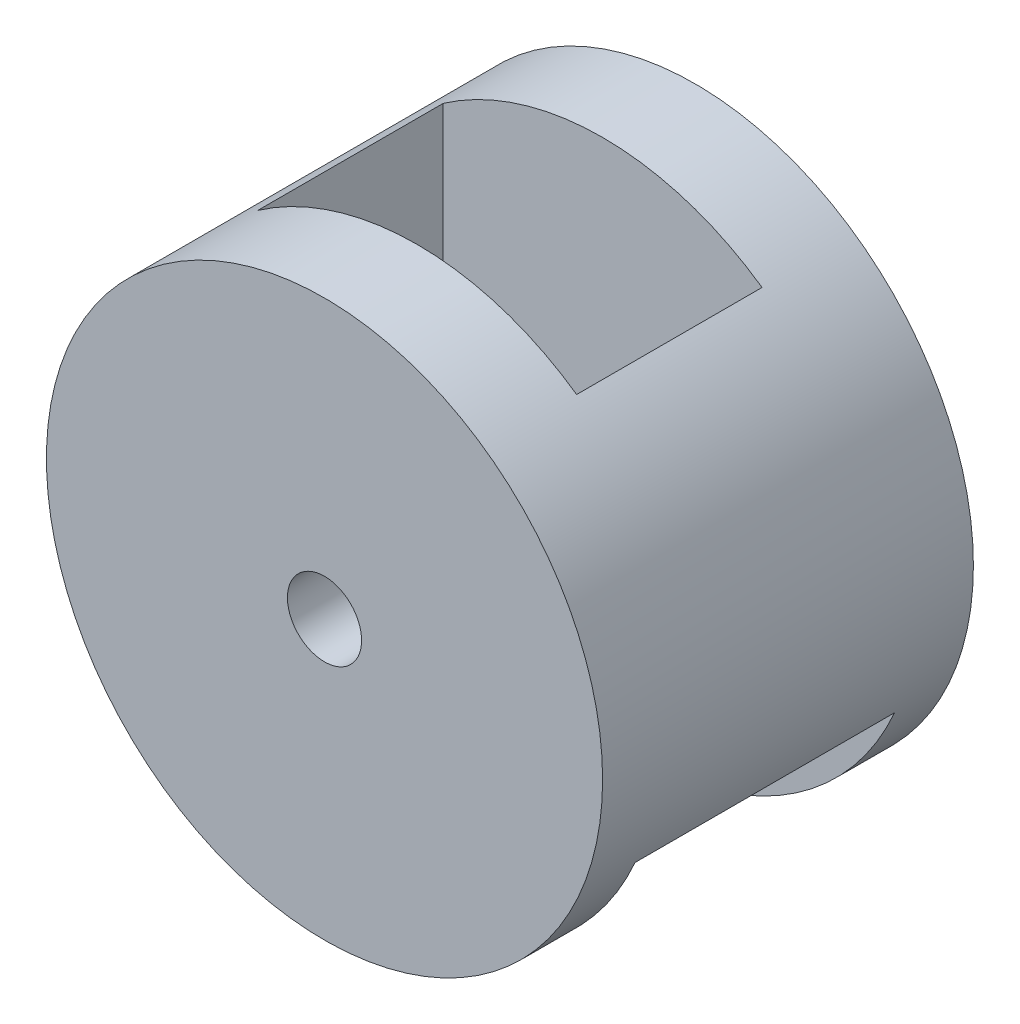
SolidWorks part; units mm, degrees
ref_plane "前视基准面" through (0, 0, 0) normal (0, 0, 1) x (1, 0, 0)
ref_plane "上视基准面" through (0, 0, 0) normal (0, 1, 0) x (1, 0, 0)
ref_plane "右视基准面" through (0, 0, 0) normal (1, 0, 0) x (0, 0, -1)
sketch "草图1" plane through (0, 0, 0) normal (0, 0, 1) x (1, 0, 0)
  circle A0 centre (0, 0) radius 7.5
  dimension "D1" = 15
extrude "凸台-拉伸1" add sketch "草图1" along normal blind 10
ref_plane "基准面4" through (0, 0, 2.5) normal (0, 0, -1) x (-1, 0, 0)
sketch "草图2" plane through (0, 0, 2.5) normal (0, 0, -1) x (-1, 0, 0)
  line L0 (-4.3, 0) -> (-4.3, 6.1449)
  line L1 (4.3, 0) -> (4.3, 6.1449)
  arc A0 (-4.3, 0) -> (4.3, 0) centre (0, 0) ccw
  circle A1 centre (0, 0) radius 7.5 construction
  arc A2 (4.3, 6.1449) -> (-4.3, 6.1449) centre (0, 0) ccw
  dimension "D1" = 8.6
extrude "切除-拉伸1" cut sketch "草图2" against normal blind 5 contours A2 L0 A0 L1
sketch "草图3" plane through (0, 0, 0) normal (0, 0, -1) x (-1, 0, 0)
  circle A0 centre (0, 0) radius 1
  dimension "D1" = 2
extrude "切除-拉伸2" cut sketch "草图3" against normal through all
ref_plane "基准面5" through (0, 0, 1.5) normal (0, 0, -1) x (-1, 0, 0)
sketch "草图5" plane through (0, 0, 1.5) normal (0, 0, -1) x (-1, 0, 0)
  line L1 (-5.7663, -3) -> (-6.8739, -3)
  line L2 (5.7663, -3) -> (6.8739, -3)
  arc A0 (-6.8739, -3) -> (6.8739, -3) centre (0, 0) ccw
  arc A1 (-5.7663, -3) -> (5.7663, -3) centre (0, 0) ccw
  dimension "D1" = 13
extrude "切除-拉伸3" cut sketch "草图5" against normal blind 7
